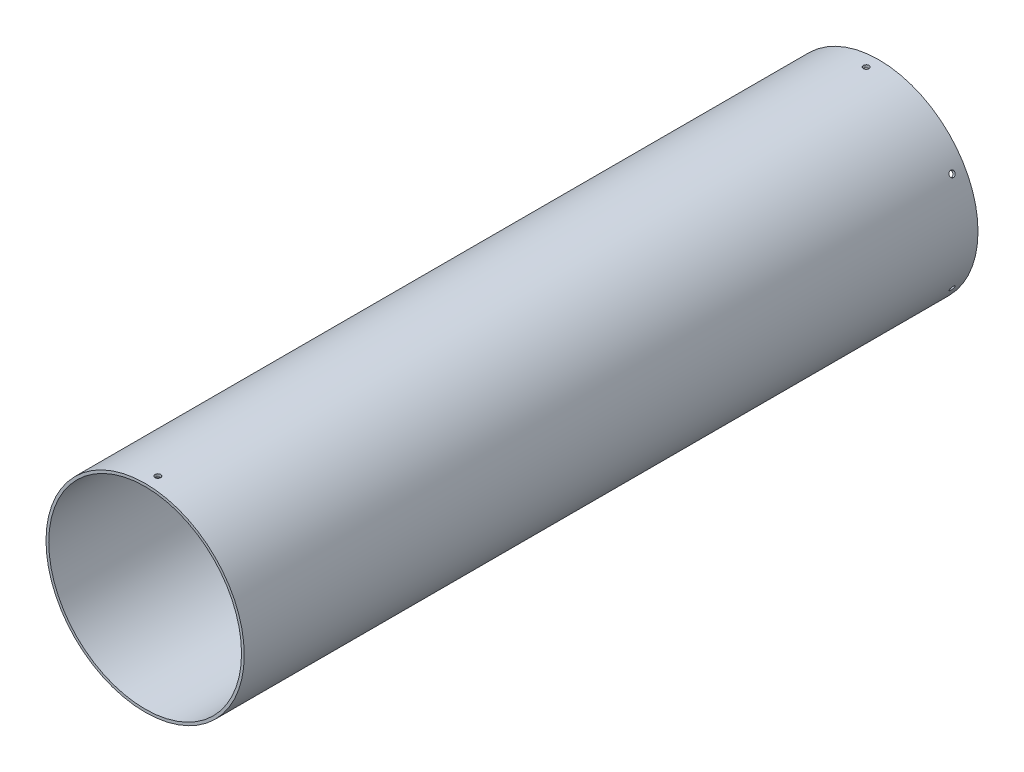
SolidWorks part; units mm, degrees
material "A-Glass Fiber"
ref_plane "Front Plane" through (0, 0, 0) normal (0, 0, 1) x (1, 0, 0)
ref_plane "Top Plane" through (0, 0, 0) normal (0, 1, 0) x (1, 0, 0)
ref_plane "Right Plane" through (0, 0, 0) normal (1, 0, 0) x (0, 0, -1)
sketch "Sketch1" plane through (0, 0, 0) normal (0, 0, 1) x (1, 0, 0)
  circle A0 centre (0, 0) radius 76.2
  circle A1 centre (0, 0) radius 78.359
  dimension "D1" = 156.718
  dimension "D2" = 152.4
extrude "Boss-Extrude1" add sketch "Sketch1" along normal blind 580
sketch "Sketch4" plane through (0, 0, 0) normal (0, 1, 0) x (1, 0, 0)
  line L0 (78.359, 0) -> (-78.359, 0) construction
  point P0 (0, -10)
  dimension "D1" = 10
hole_wizard "M4 Clearance Hole2" positions "Sketch4" profile "Sketch5" hole size "M4" standard "ANSI Metric"
sketch "Sketch5" plane through (0, 0, 10) normal (1, 0, 0) x (0, 0, 1)
  line L0 (0, 0) -> (0, 78.359)
  line L1 (0, 78.359) -> (2.25, 78.359)
  line L2 (2.25, 78.359) -> (2.25, 0)
  line L5 (2.25, 0) -> (0, 0)
  line L11 (0, -6.35) -> (0, 107.95) construction
  dimension "Thru Hole Dia." = 4.5
  dimension "Thru Hole Depth" = 78.359
pattern_circular "CirPattern1" count 6 over 360 about axis through (0, 0, 580) along (0, 0, -1) of "M4 Clearance Hole2"
sketch "Sketch6" plane through (0, 0, 0) normal (0, 1, 0) x (1, 0, 0)
  line L0 (-78.359, -580) -> (78.359, -580) construction
  point P0 (0, -570)
  dimension "D1" = 10
hole_wizard "M4 Clearance Hole3" positions "Sketch6" profile "Sketch7" hole size "M4" standard "ANSI Metric"
sketch "Sketch7" plane through (0, 0, 570) normal (1, 0, 0) x (0, 0, -1)
  line L0 (0, 0) -> (0, 78.359)
  line L1 (0, 78.359) -> (2.25, 78.359)
  line L2 (2.25, 78.359) -> (2.25, 0)
  line L5 (2.25, 0) -> (0, 0)
  line L11 (0, -6.35) -> (0, 107.95) construction
  dimension "Thru Hole Dia." = 4.5
  dimension "Thru Hole Depth" = 78.359
